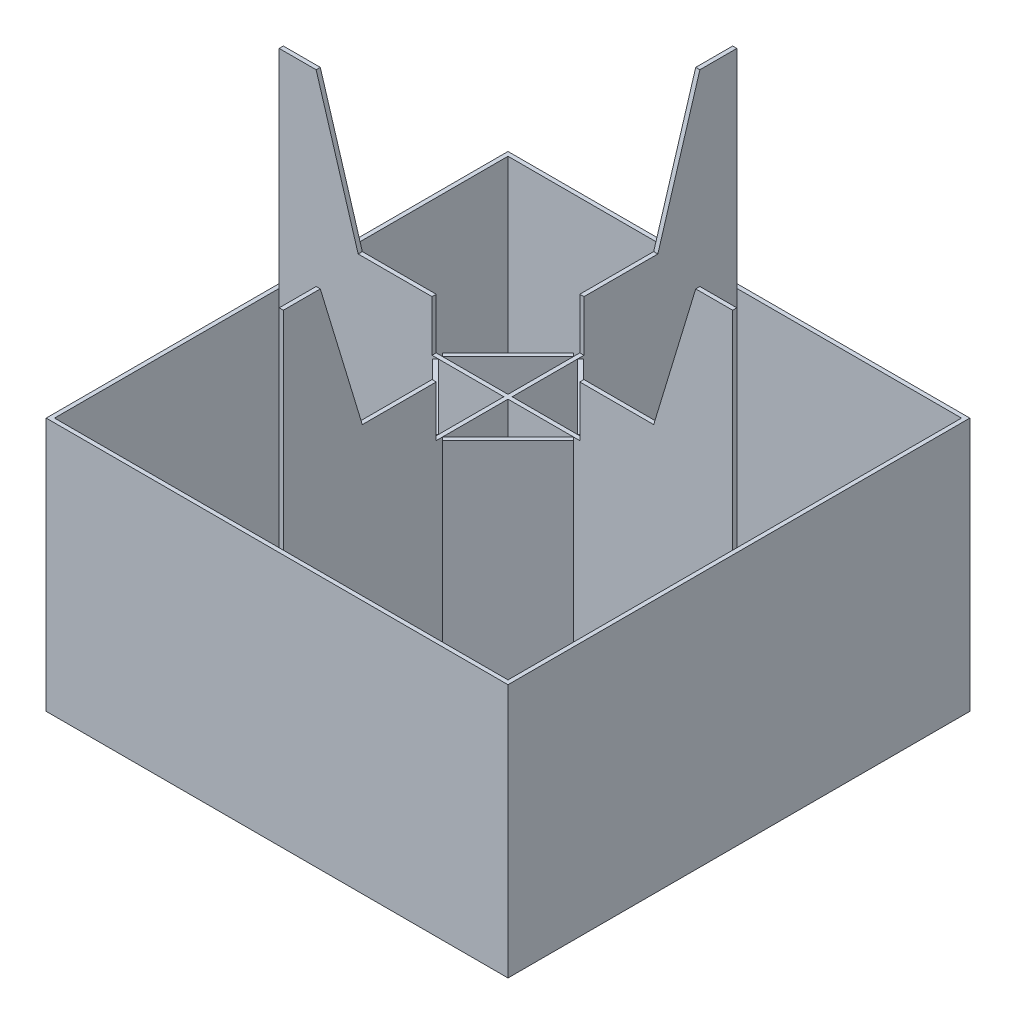
SolidWorks part; units mm, degrees
ref_plane "Front Plane" through (0, 0, 0) normal (0, 0, 1) x (1, 0, 0)
ref_plane "Top Plane" through (0, 0, 0) normal (0, 1, 0) x (1, 0, 0)
ref_plane "Right Plane" through (0, 0, 0) normal (1, 0, 0) x (0, 0, -1)
sketch "Sketch1" plane through (0, 0, 0) normal (0, 1, 0) x (1, 0, 0)
  line L16 (-2.25, 2.25) -> (2.25, -2.25) construction
  line L17 (-1027.5, 0) -> (-300, 0) construction
  line L31 (300, 0) -> (49972.5, 0) construction
  line L40 (-245.5, 245.5) -> (-2.25, 245.5)
  line L41 (-245.5, 245.5) -> (-245.5, 2.25)
  line L46 (-245.5, 2.25) -> (-2.25, 2.25)
  line L67 (-2.25, 245.5) -> (-2.25, 2.25)
  line L68 (2.25, 245.5) -> (245.5, 245.5)
  line L69 (2.25, 245.5) -> (2.25, 2.25)
  line L70 (2.25, 2.25) -> (245.5, 2.25)
  line L71 (245.5, 245.5) -> (245.5, 2.25)
  line L72 (-245.5, -2.25) -> (-2.25, -2.25)
  line L73 (-245.5, -2.25) -> (-245.5, -245.5)
  line L77 (-245.5, -245.5) -> (-2.25, -245.5)
  line L98 (-2.25, -2.25) -> (-2.25, -245.5)
  line L99 (2.25, -2.25) -> (245.5, -2.25)
  line L100 (2.25, -2.25) -> (2.25, -245.5)
  line L101 (2.25, -245.5) -> (245.5, -245.5)
  line L102 (245.5, -2.25) -> (245.5, -245.5)
  line L103 (-250, 250) -> (250, 250)
  line L104 (-250, 250) -> (-250, -250)
  line L105 (-250, -250) -> (250, -250)
  line L106 (250, 250) -> (250, -250)
  point P22 (0, 0)
  point P25 (0, 0)
  dimension "D1" = 4.5
  dimension "D2" = 4.5
  dimension "D3" = 4.5
  dimension "D4" = 4.5
  dimension "D6" = 4.5
  dimension "D7" = 500
  dimension "D5" = 4.5
extrude "Boss-Extrude1" add sketch "Sketch1" along normal blind 500
sketch "Sketch4" plane through (0, 500, 0) normal (0, 1, 0) x (1, 0, 0)
  line L0 (-129.4611, 135.8313) -> (-126.9611, 133.3313) construction
  line L1 (711.5419, 711.5419) -> (-1, -1) construction
  line L3 (-128.8203, -1) -> (-69.7107, -1) construction
  line L4 (5.432, 76.1427) -> (76.1427, 5.432)
  line L7 (-76.1427, 5.432) -> (-5.432, 76.1427)
  line L9 (2.25, 72.9607) -> (72.9607, 2.25)
  line L12 (-72.9607, 2.25) -> (-2.25, 72.9607)
  line L13 (-250, 250) -> (250, 250) construction
  line L14 (-72.9607, 2.25) -> (-76.1427, 5.432)
  line L15 (-245.5, 2.25) -> (-2.25, 2.25) construction
  line L18 (-1, -1) -> (7.3703, -1) construction
  line L19 (-2.25, 72.9607) -> (-5.432, 76.1427)
  line L20 (-2.25, 245.5) -> (-2.25, 2.25) construction
  line L21 (2.25, 72.9607) -> (5.432, 76.1427)
  line L22 (2.25, 245.5) -> (2.25, 2.25) construction
  line L23 (1, 69.7107) -> (1, 50134.5813) construction
  line L24 (72.9607, 2.25) -> (76.1427, 5.432)
  line L25 (2.25, 2.25) -> (245.5, 2.25) construction
  line L32 (-1, -1) -> (1, 5.3703) construction
  point P4 (0, 0)
  point P12 (1, -1)
  point P21 (0, 250)
  dimension "D2" = 4.5
  dimension "D3" = 4.5
  dimension "D1" = 100
extrude "Boss-Extrude3" add sketch "Sketch4" against normal up to surface (500 mm away) up to face at (0, 0, 0)
ref_plane "Plane1" through (0, 0, 0) normal (0, 0, 1) x (1, 0, 0)
sketch "Sketch8" plane through (0, 500, 0) normal (0, 1, 0) x (1, 0, 0)
  line L1 (-245.5, 245.5) -> (245.5, 245.5)
  line L2 (-245.5, 245.5) -> (-245.5, -245.5)
  line L3 (-245.5, -245.5) -> (245.5, -245.5)
  line L4 (-250, -250) -> (250, -250)
  line L5 (250, -250) -> (250, 250)
  line L6 (250, 250) -> (-250, 250)
  line L7 (-250, 250) -> (-250, -250)
  line L8 (-250, -250) -> (250, -250)
  line L9 (250, -250) -> (250, 250)
  line L10 (250, 250) -> (-250, 250)
  line L11 (-250, 250) -> (-250, -250)
  line L12 (245.5, 245.5) -> (245.5, -245.5)
  dimension "D1" = 0
sketch "Sketch10" plane through (0, 0, 0) normal (0, 0, 1) x (1, 0, 0)
  line L0 (0, 0) -> (0, 50000) construction
mirror "Mirror2" about plane through (0, 0, 0) normal (0, 0, 1) of bodies 111 110
extrude "Cut-Extrude1" cut sketch "Sketch8" against normal blind 225
sketch "Sketch11" plane through (0, 0, 0) normal (0, 0, 1) x (1, 0, 0)
  line L1 (205.5, 500) -> (160, 350)
  line L2 (160, 350) -> (80, 350)
  line L3 (80, 350) -> (80, 295)
  line L4 (205.5, 500) -> (0, 500)
  line L5 (0, -200000) -> (0, 250000) construction
  line L6 (2.25, 500) -> (245.5, 500) construction
  line L18 (0, 500) -> (0, 295)
  line L19 (0, 295) -> (80, 295)
  dimension "D3" = 80
  dimension "D4" = 150
  dimension "D5" = 55
revolve "Cut-Revolve3" cut sketch "Sketch11" angle 360 about L18
ref_plane "Plane2" through (0, 295, 0) normal (0, 1, 0) x (1, 0, 0)
